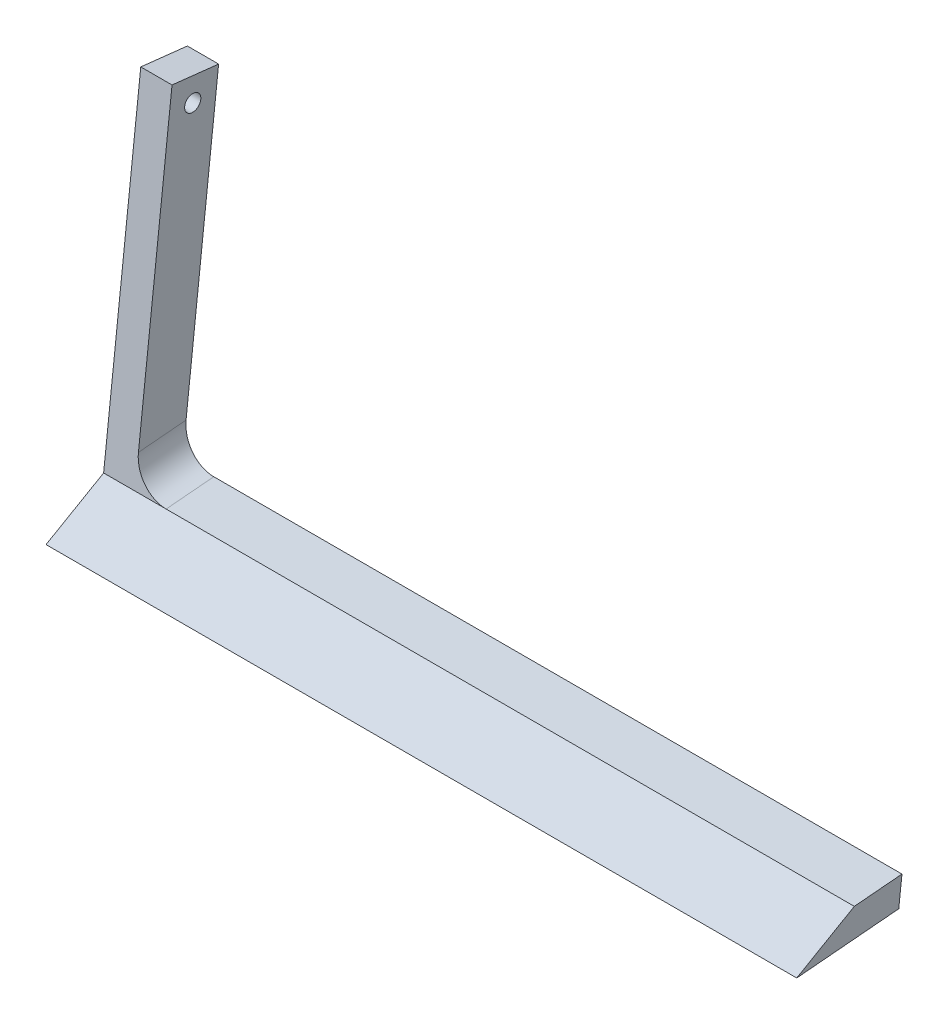
SolidWorks part; units mm, degrees
ref_plane "Front Plane" through (0, 0, 0) normal (0, 0, 1) x (1, 0, 0)
ref_plane "Top Plane" through (0, 0, 0) normal (0, 1, 0) x (1, 0, 0)
ref_plane "Right Plane" through (0, 0, 0) normal (1, 0, 0) x (0, 0, -1)
sketch "Sketch1" plane through (-0.2411, 0, 0) normal (1, 0, 0) x (0, 0, -1)
  line L0 (-315.4677, 294.7268) -> (-335.9977, 294.7268)
  line L1 (-335.9977, 294.7268) -> (-324.2987, 301.4813)
  line L2 (-273.37, 294.7268) -> (-348.5587, 294.7268) construction
  line L3 (-279.3588, 297.9018) -> (-278.0401, 297.9018) construction
  line L4 (-315.4677, 294.7268) -> (-307.2886, 368.0903)
  line L5 (-307.2886, 368.0903) -> (-316.7549, 369.1457)
  line L6 (-316.7549, 369.1457) -> (-324.2987, 301.4813)
  line L7 (-315.2655, 296.5407) -> (-335.9977, 294.7268)
  line L8 (-307.8163, 363.3571) -> (-317.2826, 364.4125) construction
  line L9 (-317.2826, 364.4125) -> (-312.5495, 363.8848) construction
  line L10 (-312.5495, 363.8848) -> (-312.0218, 368.618) construction
  circle A0 centre (-312.5495, 363.8848) radius 73.025 construction
  circle A1 centre (-312.5495, 363.8848) radius 63.5 construction
  circle A2 centre (-312.5495, 363.8848) radius 2.35
  circle M14 centre (-312.5495, 344.1848) radius 0.5
  line M19 (-322.5495, 336.6848) -> (-302.5495, 336.6848)
  arc M21 (-315.5493, 358.1193) -> (-316.1246, 359.3177) centre (-317.0492, 358.1366) ccw
  arc M22 (-316.1246, 359.3177) -> (-308.9743, 359.3177) centre (-312.5495, 363.8848) cw
  arc M23 (-308.9743, 359.3177) -> (-309.5497, 358.1193) centre (-308.0498, 358.1366) ccw
  arc M24 (-309.5497, 358.1193) -> (-315.5493, 358.1193) centre (-312.5495, 358.0848) cw
  dimension "D3" = 127
  dimension "D4" = 146.05
  dimension "D8" = 4.7
  dimension "D1" = 30
  dimension "D2" = 3.175
  dimension "D5" = 5
  dimension "D6" = 9.525
  dimension "D7" = 4.7625
extrude "Boss-Extrude1" add sketch "Sketch1" along normal blind 6.35 contours L7 L4 L6 L1 M19 | L6 L4 M22 M19 M23 M24 M21 M14 | L6 L4 L5 A2 M22 M21 M24 M23 | L4 L5 M22 | L5 L6 M22 | M14
sketch "Sketch2" plane through (6.1089, 0, 0) normal (1, 0, 0) x (0, 0, -1)
  line L0 (-324.2987, 301.4813) -> (-314.6203, 302.328)
  line L1 (-315.2655, 296.5407) -> (-307.2886, 368.0903) construction
  line L2 (-315.2655, 296.5407) -> (-335.9977, 294.7268) construction
  line L3 (-335.9977, 294.7268) -> (-324.2987, 301.4813) construction
  line L4 (-315.2655, 296.5407) -> (-314.6203, 302.328)
  line L5 (-315.2655, 296.5407) -> (-335.9977, 294.7268)
  line L6 (-335.9977, 294.7268) -> (-324.2987, 301.4813)
extrude "Boss-Extrude2" add sketch "Sketch2" along normal up to surface (146.15 mm away)
fillet "Fillet1" radius 6.35 1 edges at (6.1089, 301.9046, 319.4595)
sketch "Sketch3" plane through (6.1089, 0, 0) normal (1, 0, 0) x (0, 0, -1)
  circle A0 centre (-312.5495, 363.8848) radius 1.65
  circle A1 centre (-312.5495, 363.8848) radius 2.35 construction
  circle A2 centre (-312.5495, 363.8848) radius 2.35
  dimension "D1" = 3.3
extrude "Boss-Extrude3" add sketch "Sketch3" against normal blind 3.175
